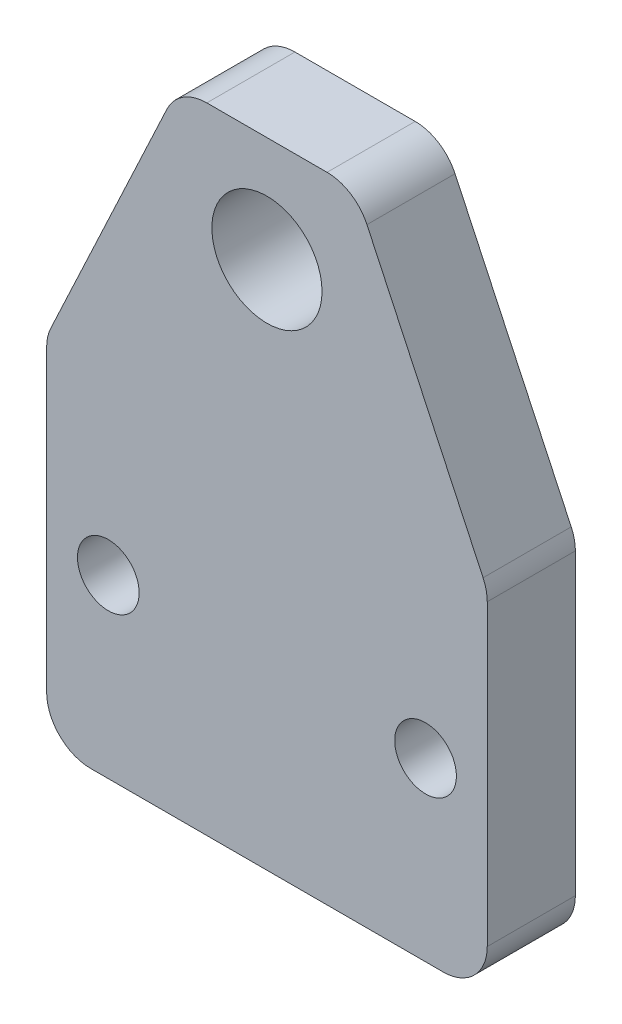
SolidWorks part; units mm, degrees
ref_plane "Plan de face" through (0, 0, 0) normal (0, 0, 1) x (1, 0, 0)
ref_plane "Plan de dessus" through (0, 0, 0) normal (0, 1, 0) x (1, 0, 0)
ref_plane "Plan de droite" through (0, 0, 0) normal (1, 0, 0) x (0, 0, -1)
sketch "Esquisse1" plane through (0, 0, 0) normal (0, 0, 1) x (1, 0, 0)
  line L0 (-25, 0) -> (25, 0)
  line L1 (25, 0) -> (25, 40)
  line L2 (25, 40) -> (10, 72)
  line L3 (10, 72) -> (-10, 72)
  line L4 (0, 72) -> (0, 0) construction
  line L5 (-25, 40) -> (-10, 72)
  line L6 (-25, 0) -> (-25, 40)
  dimension "D1" = 40
  dimension "D2" = 72
  dimension "D3" = 20
  dimension "D4" = 50
extrude "Boss.-Extru.1" add sketch "Esquisse1" along normal blind 10
sketch "Esquisse2" plane through (0, 0, 10) normal (0, 0, 1) x (1, 0, 0)
  line L0 (-25, 20) -> (25, 20) construction
  line L1 (-25, 40) -> (-25, 0) construction
  line L2 (25, 0) -> (25, 40) construction
  line L3 (0, 0) -> (0, 20) construction
  circle A0 centre (18, 20) radius 3.5
  circle A1 centre (-18, 20) radius 3.5
  dimension "D1" = 7
  dimension "D2" = 36
extrude "Enlèv. mat.-Extru.1" cut sketch "Esquisse2" against normal through all both and the other way through all
fillet "Congé1" radius 5 6 edges at (-25, 0, 5) (25, 0, 5) (25, 40, 5) (10, 72, 5) (-10, 72, 5) (-25, 40, 5)
sketch "Esquisse3" plane through (0, 0, 10) normal (0, 0, 1) x (1, 0, 0)
  line L0 (0, 72) -> (0, 0) construction
  line L1 (6.8217, 72) -> (-6.8217, 72) construction
  line L2 (-20, 0) -> (20, 0) construction
  circle A0 centre (0, 60) radius 6.25
  dimension "D1" = 12.5
  dimension "D2" = 60
extrude "Enlèv. mat.-Extru.2" cut sketch "Esquisse3" against normal through all
